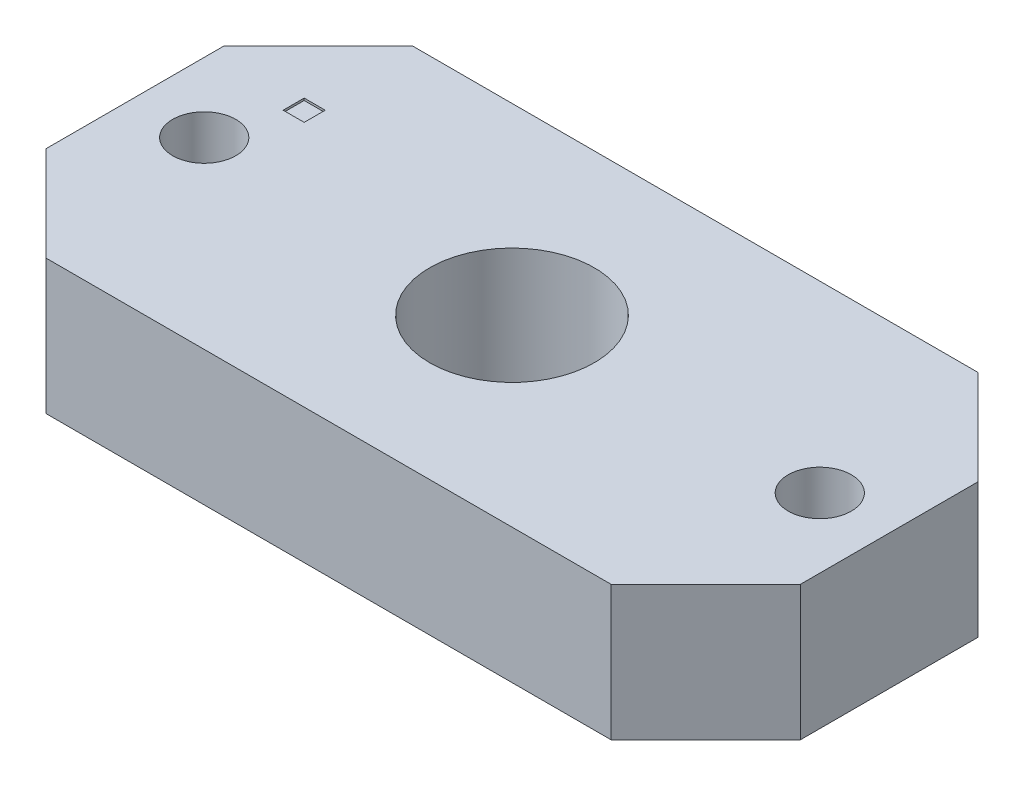
SolidWorks part; units mm, degrees
ref_plane "Front Plane" through (0, 0, 0) normal (0, 0, 1) x (1, 0, 0)
ref_plane "Top Plane" through (0, 0, 0) normal (0, 1, 0) x (1, 0, 0)
ref_plane "Right Plane" through (0, 0, 0) normal (1, 0, 0) x (0, 0, -1)
sketch "Sketch1" plane through (0, 0, 0) normal (0, 1, 0) x (1, 0, 0)
  line L0 (84.3659, 17.6585) -> (93.7763, 17.6585) construction
  line L1 (93.7763, -3.3283) -> (106.2976, 3.2433) construction
  line L2 (84.3659, -3.3283) -> (93.7763, -3.3283) construction
  line L3 (74.4461, 7.1651) -> (103.6961, 7.1651) construction
  line L4 (93.7763, 17.6585) -> (106.2976, 11.0869) construction
  line L5 (102.4961, 15.8835) -> (106.9961, 11.3835)
  line L6 (102.4961, 15.8835) -> (75.6461, 15.8835)
  line L7 (106.9961, 2.9467) -> (106.9961, 11.3835)
  line L8 (71.1461, 2.9467) -> (71.1461, 11.3835)
  line L9 (75.6461, 15.8835) -> (71.1461, 11.3835)
  line L10 (84.3659, 17.6585) -> (71.8446, 11.0869) construction
  line L11 (92.9836, 7.1651) -> (85.1586, 7.1651) construction
  line L12 (102.4961, -1.5533) -> (106.9961, 2.9467)
  line L13 (102.4961, -1.5533) -> (75.6461, -1.5533)
  line L14 (75.6461, -1.5533) -> (71.1461, 2.9467)
  line L15 (84.3659, -3.3283) -> (71.8446, 3.2433) construction
  circle A0 centre (89.0711, 7.1651) radius 3.9125
  arc A1 (106.2976, 11.0869) -> (106.2976, 3.2433) centre (103.1961, 7.1651) cw construction
  circle A22 centre (74.4461, 7.1651) radius 1.5
  circle A23 centre (103.6961, 7.1651) radius 1.5
  arc A24 (71.8446, 11.0869) -> (71.8446, 3.2433) centre (74.9461, 7.1651) ccw construction
  point P15 (107.9961, 6.9651)
  point P18 (70.1461, 6.9651)
  dimension "D23" = 3
  dimension "D3" = 7.825
extrude "Boss-Extrude1" add sketch "Sketch1" along normal blind 6.4
sketch "Sketch2" plane through (0, 6.4, 0) normal (0, 1, 0) x (1, 0, 0)
  line L0 (75.196, 10.1651) -> (76.196, 10.1651)
  line L4 (76.196, 10.1651) -> (76.196, 11.1651)
  line L5 (76.196, 11.1651) -> (75.196, 11.1651)
  line L6 (75.196, 10.1651) -> (75.196, 11.1651)
  dimension "D3" = 1
  dimension "D4" = 1
extrude "Cut-Extrude1" cut sketch "Sketch2" against normal blind 0.1
